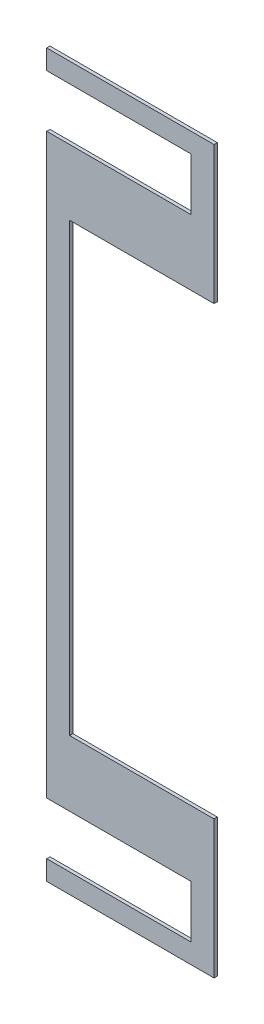
SolidWorks part; units mm, degrees
ref_plane "Front Plane" through (0, 0, 0) normal (1, 0, 0) x (0, 1, 0)
ref_plane "Top Plane" through (0, 0, 0) normal (0, 0, 1) x (0, 1, 0)
ref_plane "Right Plane" through (0, 0, 0) normal (0, 1, 0) x (-1, 0, 0)
sketch "Sketch1" plane through (0, 0, 0) normal (0, 0, 1) x (0, 1, 0)
  line L0 (565.15, 0) -> (565.15, -22.225) construction
  line L1 (0, 0) -> (19.05, 0) construction
  line L2 (0, 0) -> (0, -161.925) construction
  line L3 (0, -161.925) -> (19.05, -161.925) construction
  line L4 (19.05, 0) -> (19.05, -161.925) construction
  line L5 (19.05, -161.925) -> (69.85, -161.925) construction
  line L6 (19.05, -161.925) -> (19.05, -139.7) construction
  line L7 (19.05, -139.7) -> (69.85, -139.7) construction
  line L8 (69.85, -161.925) -> (69.85, -139.7) construction
  line L9 (69.85, -161.925) -> (133.35, -161.925) construction
  line L10 (69.85, -161.925) -> (69.85, 0) construction
  line L11 (69.85, 0) -> (133.35, 0) construction
  line L12 (133.35, -161.925) -> (133.35, 0) construction
  line L13 (133.35, 0) -> (565.15, 0) construction
  line L14 (133.35, 0) -> (133.35, -22.225) construction
  line L15 (133.35, -22.225) -> (565.15, -22.225) construction
  line L16 (349.25, 0) -> (349.25, -22.225) construction
  line L17 (565.15, -161.925) -> (565.15, 0) construction
  line L18 (628.65, 0) -> (565.15, 0) construction
  line L19 (628.65, -161.925) -> (628.65, 0) construction
  line L20 (628.65, -161.925) -> (565.15, -161.925) construction
  line L21 (628.65, -161.925) -> (628.65, -139.7) construction
  line L22 (679.45, -139.7) -> (628.65, -139.7) construction
  line L23 (679.45, -161.925) -> (679.45, -139.7) construction
  line L24 (679.45, -161.925) -> (628.65, -161.925) construction
  line L25 (679.45, 0) -> (679.45, -161.925) construction
  line L26 (698.5, -161.925) -> (679.45, -161.925) construction
  line L27 (698.5, 0) -> (698.5, -161.925) construction
  line L28 (698.5, 0) -> (679.45, 0) construction
  line L29 (0, 0) -> (0, -161.925)
  line L30 (0, -161.925) -> (133.35, -161.925)
  line L31 (133.35, -161.925) -> (133.35, -22.225)
  line L32 (133.35, -22.225) -> (565.15, -22.225)
  line L33 (565.15, -22.225) -> (565.15, -161.925)
  line L34 (565.15, -161.925) -> (698.5, -161.925)
  line L35 (698.5, -161.925) -> (698.5, 0)
  line L36 (698.5, 0) -> (679.45, 0)
  line L37 (679.45, 0) -> (679.45, -139.7)
  line L38 (679.45, -139.7) -> (628.65, -139.7)
  line L39 (628.65, -139.7) -> (628.65, 0)
  line L40 (628.65, 0) -> (69.85, 0)
  line L41 (69.85, 0) -> (69.85, -139.7)
  line L42 (69.85, -139.7) -> (19.05, -139.7)
  line L43 (19.05, -139.7) -> (19.05, 0)
  line L44 (19.05, 0) -> (0, 0)
  dimension "D1" = 161.925
  dimension "D2" = 19.05
  dimension "D3" = 22.225
  dimension "D4" = 50.8
  dimension "D5" = 63.5
  dimension "D6" = 279.4
  dimension "D7" = 22.225
extrude "Boss-Extrude1" add sketch "Sketch1" along normal blind 3.175
